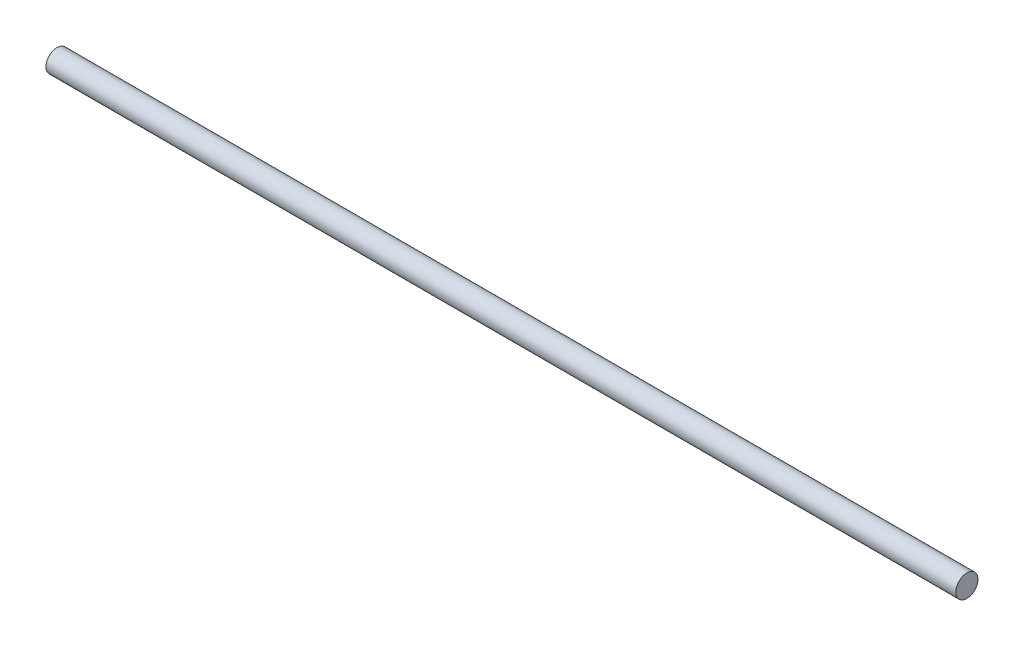
SolidWorks part; units mm, degrees
material "普通碳钢"
ref_plane "前视基准面" through (0, 0, 0) normal (0, 0, 1) x (1, 0, 0)
ref_plane "上视基准面" through (0, 0, 0) normal (0, 1, 0) x (1, 0, 0)
ref_plane "右视基准面" through (0, 0, 0) normal (1, 0, 0) x (0, 0, -1)
sketch "草图1" plane through (0, 0, 0) normal (1, 0, 0) x (0, 0, -1)
  circle A0 centre (0, 0) radius 3
  dimension "D1" = 6
extrude "凸台-拉伸1" add sketch "草图1" along normal blind 246
cosmetic thread "装饰螺纹线1"
